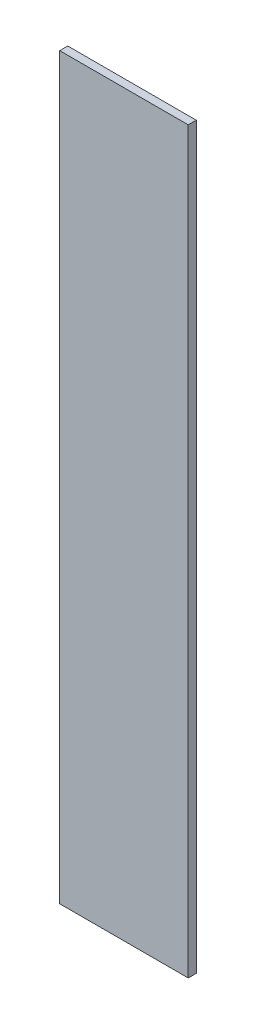
SolidWorks part; units mm, degrees
ref_plane "Front Plane" through (0, 0, 0) normal (0, 0, 1) x (1, 0, 0)
ref_plane "Top Plane" through (0, 0, 0) normal (0, 1, 0) x (1, 0, 0)
ref_plane "Right Plane" through (0, 0, 0) normal (1, 0, 0) x (0, 0, -1)
sketch "Sketch1" plane through (0, 0, 0) normal (0, 0, 1) x (1, 0, 0)
  line L1 (0, 0) -> (50.8, 0)
  line L2 (0, 0) -> (0, 292.1)
  line L3 (0, 292.1) -> (50.8, 292.1)
  line L4 (50.8, 0) -> (50.8, 292.1)
  dimension "D1" = 50.8
  dimension "D2" = 292.1
extrude "Boss-Extrude1" add sketch "Sketch1" along normal blind 3.175
